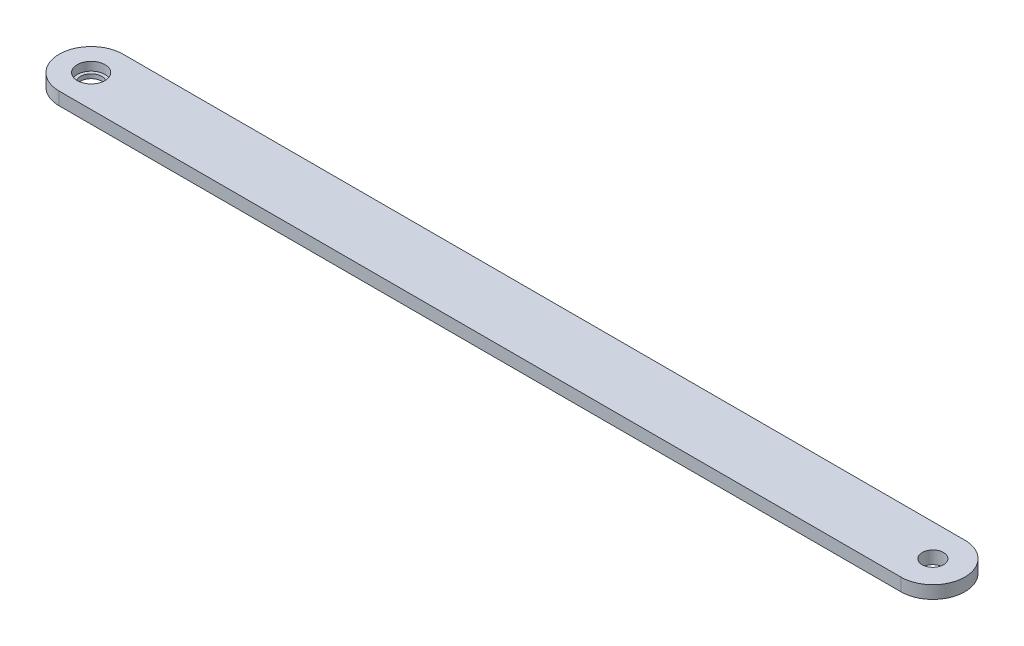
SolidWorks part; units mm, degrees
ref_plane "Front Plane" through (0, 0, 0) normal (0, 0, 1) x (1, 0, 0)
ref_plane "Top Plane" through (0, 0, 0) normal (0, 1, 0) x (1, 0, 0)
ref_plane "Right Plane" through (0, 0, 0) normal (1, 0, 0) x (0, 0, -1)
sketch "Sketch2" plane through (0, 0, 0) normal (0, 1, 0) x (1, 0, 0)
  line L1 (-45, 15) -> (350, 15)
  line L3 (-45, -15) -> (350, -15)
  arc A0 (-45, 15) -> (-45, -15) centre (-45, 0) ccw
  arc A1 (350, -15) -> (350, 15) centre (350, 0) ccw
  circle A2 centre (-45, 0) radius 5
  circle A3 centre (350, 0) radius 5
  point P0 (0, 0)
extrude "Boss-Extrude1" add sketch "Sketch2" along normal blind 6
sketch "Sketch4" plane through (0, 6, 0) normal (0, 1, 0) x (1, 0, 0)
  circle A0 centre (-45, 0) radius 6.5
extrude "Cut-Extrude2" cut sketch "Sketch4" against normal blind 4
